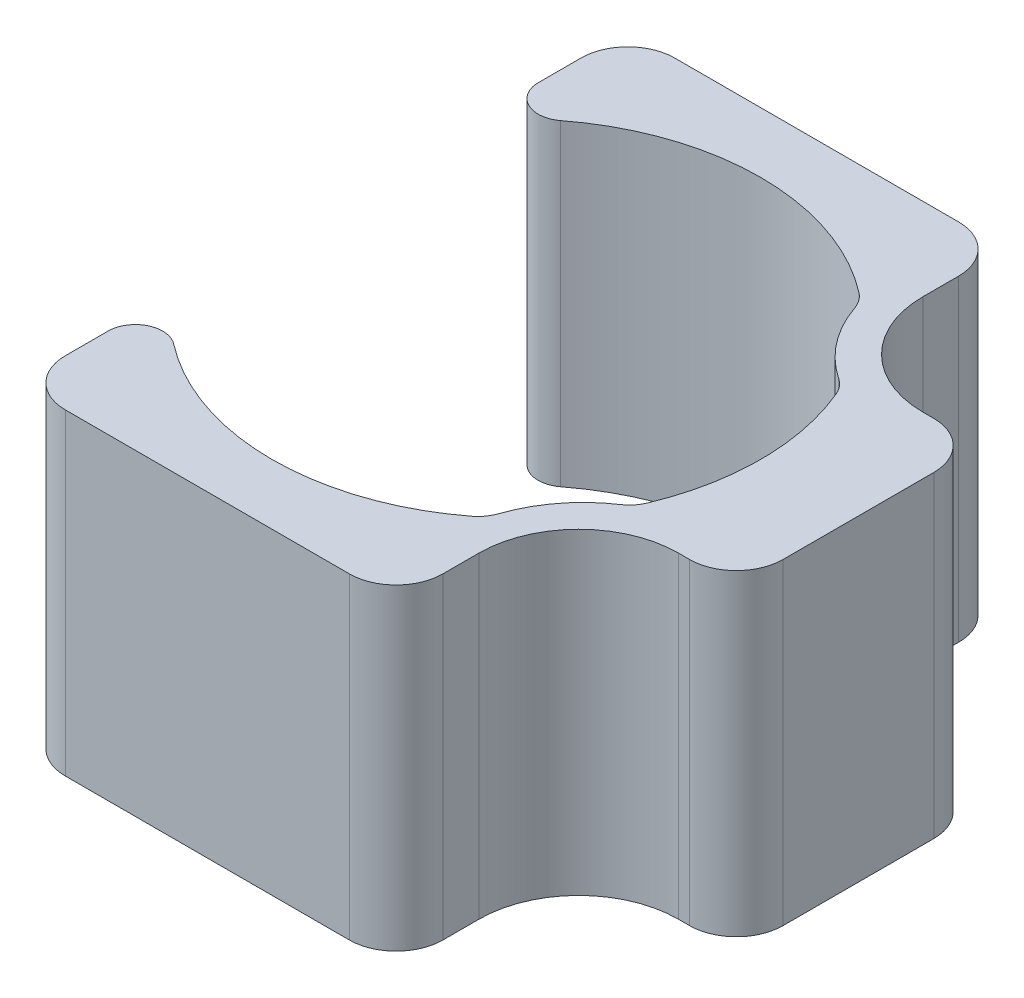
SolidWorks part; units mm, degrees
ref_plane "Front Plane" through (0, 0, 0) normal (0, 0, 1) x (1, 0, 0)
ref_plane "Top Plane" through (0, 0, 0) normal (0, 1, 0) x (1, 0, 0)
ref_plane "Right Plane" through (0, 0, 0) normal (1, 0, 0) x (0, 0, -1)
sketch "Sketch1" plane through (0, 0, 0) normal (0, 1, 0) x (1, 0, 0)
  line L0 (-61.8934, 68.9049) -> (-61.8934, 82.6209)
  line L1 (-46.8934, 97.6209) -> (44.1066, 97.6209)
  line L2 (59.1066, 82.6209) -> (59.1066, 71.1324)
  line L3 (91.1066, 39.1323) -> (94.6066, 39.1323)
  line L4 (109.6066, 24.1323) -> (109.6066, -24.1323)
  line L5 (94.6066, -39.1323) -> (91.1066, -39.1323)
  line L6 (59.1066, -71.1324) -> (59.1066, -82.6209)
  line L7 (44.1066, -97.6209) -> (-46.8934, -97.6209)
  line L8 (-61.8934, -82.6209) -> (-61.8934, -68.9049)
  arc A0 (47.8073, 61.9804) -> (-47.8073, 61.9804) centre (0, 0) ccw
  arc A1 (47.8073, 61.9804) -> (51.3214, 57.0727) centre (41.4122, 53.6894) cw
  arc A2 (51.3214, 57.0727) -> (68.3377, 34.9448) centre (92.5001, 71.1323) ccw
  arc A3 (68.3377, 34.9448) -> (72.1785, 30.2883) centre (62.5233, 26.2367) cw
  arc A4 (72.1785, -30.2883) -> (68.3377, -34.9448) centre (62.5233, -26.2367) cw
  arc A5 (68.3377, -34.9448) -> (51.3214, -57.0727) centre (92.5001, -71.1323) ccw
  arc A6 (51.3214, -57.0727) -> (47.8073, -61.9804) centre (41.4122, -53.6894) cw
  arc A7 (72.1785, -30.2883) -> (72.1785, 30.2883) centre (0, 0) ccw
  arc A8 (-47.8073, 61.9804) -> (-61.8934, 68.9049) centre (-53.1484, 68.9049) cw
  arc A9 (-61.8934, 82.6209) -> (-46.8934, 97.6209) centre (-46.8934, 82.6209) cw
  arc A10 (44.1066, 97.6209) -> (59.1066, 82.6209) centre (44.1066, 82.6209) cw
  arc A11 (59.1066, 71.1324) -> (91.1066, 39.1323) centre (91.1066, 71.1324) ccw
  arc A12 (94.6066, 39.1323) -> (109.6066, 24.1323) centre (94.6066, 24.1323) cw
  arc A13 (109.6066, -24.1323) -> (94.6066, -39.1323) centre (94.6066, -24.1323) cw
  arc A14 (91.1066, -39.1323) -> (59.1066, -71.1324) centre (91.1066, -71.1324) ccw
  arc A15 (44.1066, -97.6209) -> (59.1066, -82.6209) centre (44.1066, -82.6209) ccw
  arc A16 (-46.8934, -97.6209) -> (-61.8934, -82.6209) centre (-46.8934, -82.6209) cw
  arc A17 (-61.8934, -68.9049) -> (-47.8073, -61.9804) centre (-53.1484, -68.9049) cw
  arc A18 (-47.8073, -61.9804) -> (47.8073, -61.9804) centre (0, 0) ccw
  point P37 (59.1066, -81.2787)
  point P46 (-79.1487, -99.696)
  point P47 (0, 0)
  point P48 (0, 0)
  point P49 (0, 0)
  point P50 (0, 0)
  point P51 (-64.8801, -81.7093)
  point P52 (0, 0)
  point P54 (-58.7289, -67.3493)
  point P55 (0, 0)
  point P56 (0, 0)
  point P57 (0, 0)
  point P58 (109.6066, 0)
  dimension "D1" = 156.5518
  dimension "D2" = 43.5127
  dimension "D3" = 39.9793
  dimension "D4" = 60.5766
  dimension "D9" = 15
  dimension "D11" = 15
  dimension "D13" = 32
  dimension "D15" = 15
  dimension "D5" = 39.9793
  dimension "D6" = 27.9141
  dimension "D7" = 15.696
  dimension "D8" = 13.716
  dimension "D10" = 91
  dimension "D14" = 3.5
  dimension "D16" = 48.2647
extrude "Boss-Extrude1" add sketch "Sketch1" along normal blind 101.6
